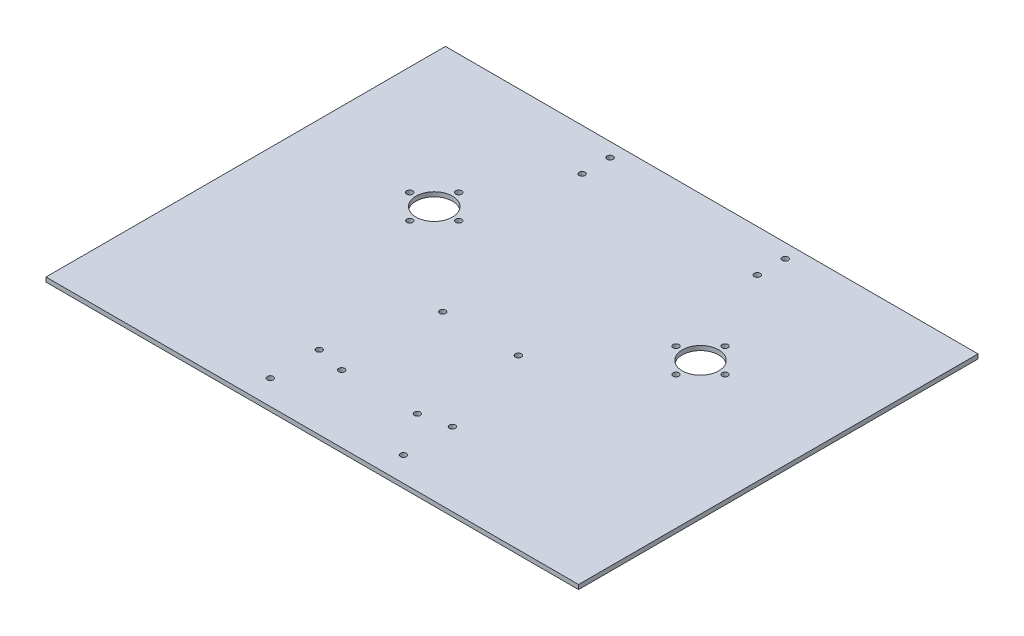
SolidWorks part; units mm, degrees
ref_plane "Front Plane" through (0, 0, 0) normal (0, 0, 1) x (1, 0, 0)
ref_plane "Top Plane" through (0, 0, 0) normal (0, 1, 0) x (1, 0, 0)
ref_plane "Right Plane" through (0, 0, 0) normal (1, 0, 0) x (0, 0, -1)
sketch "Sketch1" plane through (0, 0, 0) normal (0, 1, 0) x (1, 0, 0)
  line L0 (0, 142.5) -> (0, -142.5) construction
  line L1 (-190, -142.5) -> (190, -142.5)
  line L2 (-190, -142.5) -> (-190, 142.5)
  line L3 (-190, 142.5) -> (190, 142.5)
  line L4 (190, -142.5) -> (190, 142.5)
  line L5 (-190, -142.5) -> (190, 142.5) construction
  line L6 (-190, 142.5) -> (190, -142.5) construction
  circle A0 centre (-95, 39.5) radius 13
  circle A1 centre (-112.5, 39.5) radius 2.125
  circle A5 centre (-47.5, -125) radius 2.125
  circle A6 centre (-47.5, -90) radius 2.125
  circle A7 centre (-95, 57) radius 2.125
  circle A8 centre (-77.5, 39.5) radius 2.125
  circle A9 centre (-95, 22) radius 2.125
  circle A10 centre (-62.5, 132.5) radius 2.125
  circle A11 centre (-62.5, 112.5) radius 2.125
  circle A12 centre (47.5, -90) radius 2.125
  circle A13 centre (47.5, -125) radius 2.125
  circle A14 centre (95, 22) radius 2.125
  circle A15 centre (77.5, 39.5) radius 2.125
  circle A16 centre (112.5, 39.5) radius 2.125
  circle A17 centre (95, 57) radius 2.125
  circle A18 centre (95, 39.5) radius 13
  circle A19 centre (62.5, 112.5) radius 2.125
  circle A20 centre (62.5, 132.5) radius 2.125
  circle A21 centre (-27, -94.5) radius 2.125
  circle A22 centre (-27, -22.5) radius 2.125
  circle A23 centre (27, -94.5) radius 2.125
  circle A24 centre (27, -22.5) radius 2.125
  point P0 (0, 0)
  point P21 (-101.1247, 45.6247)
  point P26 (-95, 39.5)
  point P50 (-27, -22.5)
  dimension "D3" = 26
  dimension "D6" = 4.25
  dimension "D8" = 4.25
  dimension "D10" = 4.25
  dimension "D13" = 4.25
  dimension "D14" = 4.25
  dimension "D19" = 4.25
  dimension "D22" = 4.25
  dimension "D1" = 182
  dimension "D2" = 95
  dimension "D4" = 285
  dimension "D5" = 17.5
  dimension "D9" = 17.5
  dimension "D11" = 35
  dimension "D12" = 95
  dimension "D15" = 127.5
  dimension "D16" = 20
  dimension "D17" = 10
  dimension "D18" = 47.5
  dimension "D20" = 27
  dimension "D21" = 72
  dimension "D23" = 48
  dimension "D7" = 4
extrude "Boss-Extrude1" add sketch "Sketch1" along normal blind 3.175
